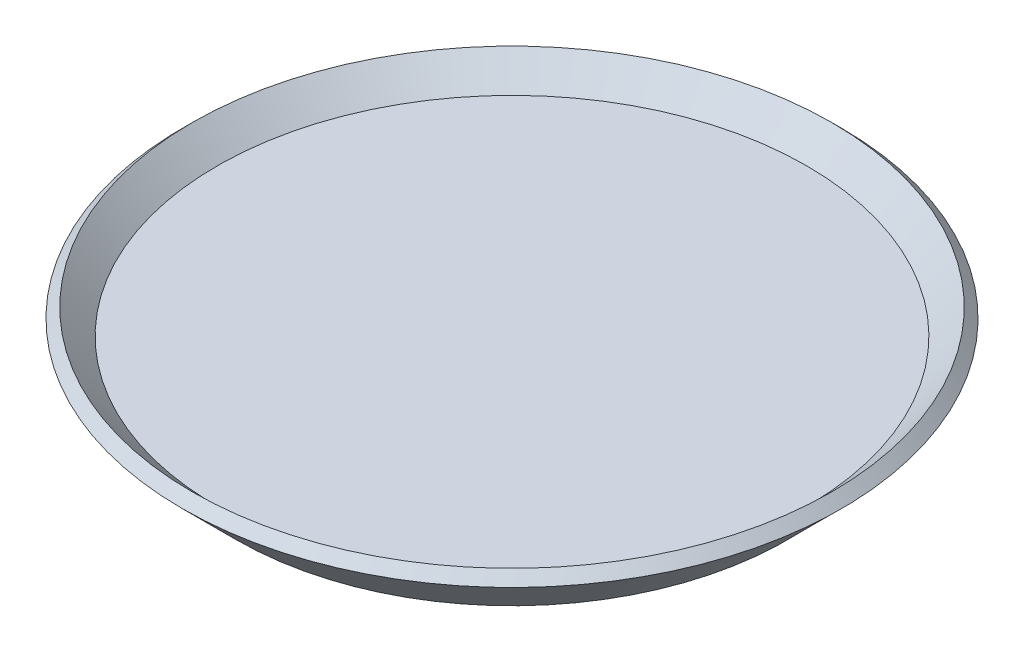
SolidWorks part; units mm, degrees
ref_plane "Front Plane" through (0, 0, 0) normal (0, 0, 1) x (1, 0, 0)
ref_plane "Top Plane" through (0, 0, 0) normal (0, 1, 0) x (1, 0, 0)
ref_plane "Right Plane" through (0, 0, 0) normal (1, 0, 0) x (0, 0, -1)
sketch "Sketch1" plane through (0, 0, 0) normal (0, 0, 1) x (1, 0, 0)
  line L0 (0, -54.675) -> (0, 85.725) construction
  line L1 (0, 0) -> (100, 0)
  line L2 (100, 0) -> (119.6183, 19.6183)
  line L3 (119.6183, 19.6183) -> (116.0828, 23.1539)
  line L4 (116.0828, 23.1539) -> (107.0059, 14.0769)
  line L5 (0, 5) -> (0, 14.0769)
  line L6 (0, 0) -> (0, 5)
  line L7 (107.0059, 14.0769) -> (0, 14.0769)
  dimension "D1" = 100
  dimension "D2" = 135
  dimension "D3" = 5
revolve "Revolve1" add sketch "Sketch1" angle 360 about L0
sketch3d "URDF Reference"
  line L0 (0, 0, 0) -> (10, 0, 0) construction
  line L1 (0, 0, 0) -> (0, 0, -10) construction
  point P0 (0, 0, 0)
  point P1 (0, 0, 0)
